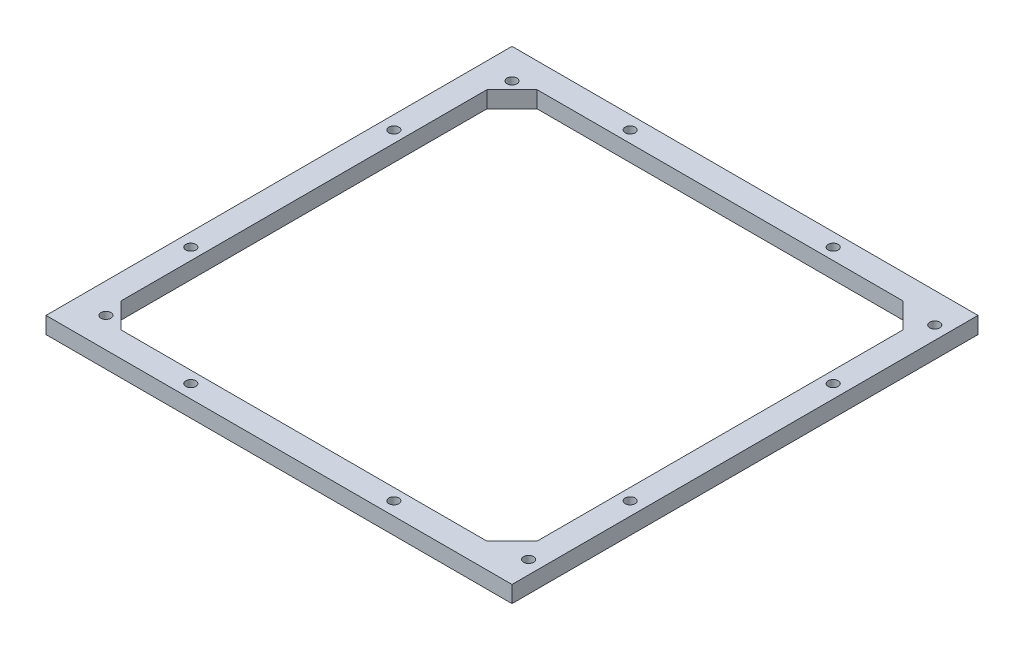
SolidWorks part; units mm, degrees
ref_plane "Alzado" through (0, 0, 0) normal (0, 0, 1) x (1, 0, 0)
ref_plane "Planta" through (0, 0, 0) normal (0, 1, 0) x (1, 0, 0)
ref_plane "Vista lateral" through (0, 0, 0) normal (1, 0, 0) x (0, 0, -1)
sketch "Croquis1" plane through (0, 0, 0) normal (0, 1, 0) x (1, 0, 0)
  line L0 (0, 0) -> (-62.5, 0) construction
  line L1 (-62.5, 0) -> (-62.5, 55) construction
  line L2 (-62.5, 55) -> (-55, 62.5) construction
  line L3 (-55, 62.5) -> (0, 62.5) construction
  line L4 (0, 62.5) -> (0, 0) construction
  line L5 (62.5, 55) -> (62.5, 0) construction
  line L6 (55, 62.5) -> (62.5, 55) construction
  line L7 (0, 62.5) -> (55, 62.5) construction
  line L8 (55, -62.5) -> (0, -62.5) construction
  line L9 (62.5, -55) -> (55, -62.5) construction
  line L10 (62.5, 0) -> (62.5, -55) construction
  line L11 (-62.5, -55) -> (-62.5, 0) construction
  line L12 (-55, -62.5) -> (-62.5, -55) construction
  line L13 (0, -62.5) -> (-55, -62.5) construction
  line L14 (0, -70) -> (0, -62.5) construction
  line L15 (0, 0) -> (-61, 0) construction
  line L16 (0, 0) -> (0, 61) construction
  line L17 (0, 61) -> (-61, 61) construction
  line L18 (-61, 0) -> (-61, 61) construction
  line L19 (0, 0) -> (-61, 0) construction
  line L20 (0, 0) -> (0, -61) construction
  line L21 (0, -61) -> (-61, -61) construction
  line L22 (-61, 0) -> (-61, -61) construction
  line L23 (0, 0) -> (66, 0) construction
  line L24 (0, 0) -> (0, -61) construction
  line L25 (0, -61) -> (66, -61) construction
  line L26 (66, 0) -> (66, -61) construction
  line L27 (0, 0) -> (66, 0) construction
  line L28 (0, 0) -> (0, 61) construction
  line L29 (0, 61) -> (66, 61) construction
  line L30 (66, 0) -> (66, 61) construction
  line L35 (25, -25) -> (-25, 25) construction
  line L36 (25, 25) -> (-25, -25) construction
  line L37 (70, -70) -> (-70, -70)
  line L38 (70, -70) -> (70, 70)
  line L39 (70, 70) -> (-70, 70)
  line L40 (-70, -70) -> (-70, 70)
  line L41 (70, -70) -> (-70, 70) construction
  line L42 (70, 70) -> (-70, -70) construction
  line L43 (-30.5, -66) -> (30.5, -66) construction
  line L44 (-55, -62.5) -> (-62.5, -55)
  line L45 (-62.5, -55) -> (-62.5, 55)
  line L46 (-62.5, 55) -> (-55, 62.5)
  line L47 (-55, 62.5) -> (55, 62.5)
  line L48 (55, 62.5) -> (62.5, 55)
  line L49 (62.5, 55) -> (62.5, -55)
  line L50 (62.5, -55) -> (55, -62.5)
  line L51 (55, -62.5) -> (-55, -62.5)
  circle A0 centre (-61, 61) radius 1.5
  circle A1 centre (66, 61) radius 1.5
  circle A2 centre (66, -61) radius 1.5
  circle A3 centre (-61, -61) radius 1.5
  circle A4 centre (66, 30.5) radius 1.5
  circle A5 centre (66, -30.5) radius 1.5
  circle A6 centre (-30.5, -66) radius 1.5
  circle A7 centre (30.5, -66) radius 1.5
  circle A8 centre (-30.5, 66) radius 1.5
  circle A9 centre (30.5, 66) radius 1.5
  circle A10 centre (-66, 30.5) radius 1.5
  circle A11 centre (-66, -30.5) radius 1.5
  point P48 (0, -66)
  dimension "D6" = 3
  dimension "D9" = 4
  dimension "D10" = 3
  dimension "D1" = 55
  dimension "D2" = 62.5
  dimension "D4" = 61
  dimension "D5" = 66
  dimension "D8" = 140
  dimension "D11" = 61
  dimension "D3" = 4
extrude "Saliente-Extruir1" add sketch "Croquis1" along normal blind 5
